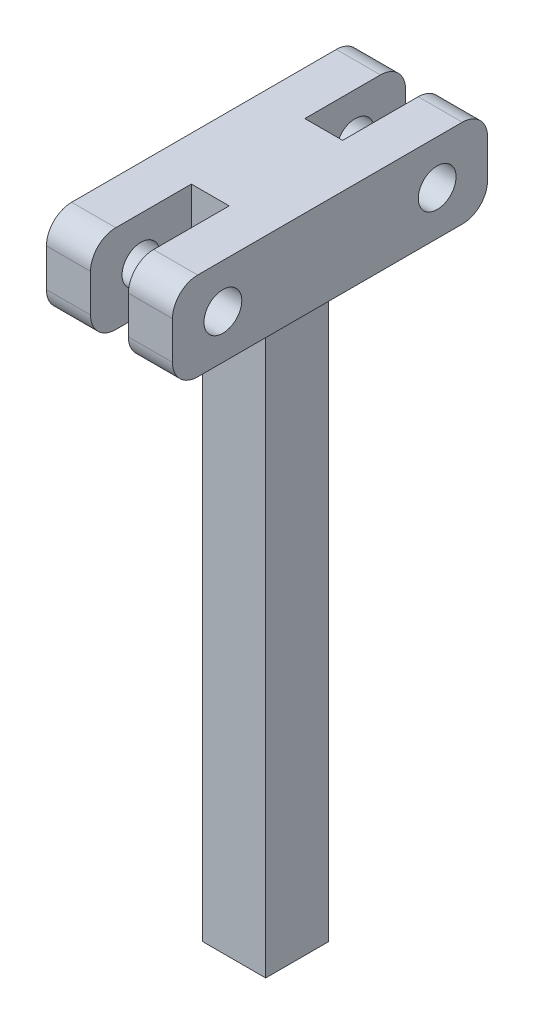
SolidWorks part; units mm, degrees
ref_plane "Alzado" through (0, 0, 0) normal (0, 0, 1) x (1, 0, 0)
ref_plane "Planta" through (0, 0, 0) normal (0, 1, 0) x (1, 0, 0)
ref_plane "Vista lateral" through (0, 0, 0) normal (1, 0, 0) x (0, 0, -1)
sketch "Croquis1" plane through (0, 0, 0) normal (0, 1, 0) x (1, 0, 0)
  line L1 (2.5, -2.6049) -> (-2.5, -2.6049)
  line L2 (2.5, -2.6049) -> (2.5, 2.3951)
  line L3 (2.5, 2.3951) -> (-2.5, 2.3951)
  line L4 (-2.5, -2.6049) -> (-2.5, 2.3951)
  line L5 (2.5, -2.6049) -> (-2.5, 2.3951) construction
  line L6 (2.5, 2.3951) -> (-2.5, -2.6049) construction
  dimension "D1" = 5
  dimension "D2" = 5
extrude "Saliente-Extruir1" add sketch "Croquis1" against normal blind 50
sketch "Croquis2" plane through (0, 0, 0) normal (1, 0, 0) x (0, 0, -1)
  line L1 (10.5, -3.5) -> (-10.5, -3.5)
  line L2 (12.5, -1.5) -> (12.5, 1.5)
  line L3 (10.5, 3.5) -> (-10.5, 3.5)
  line L4 (-12.5, -1.5) -> (-12.5, 1.5)
  line L5 (12.5, -3.5) -> (-12.5, 3.5) construction
  line L6 (12.5, 3.5) -> (-12.5, -3.5) construction
  arc A0 (-12.5, 1.5) -> (-10.5, 3.5) centre (-10.5, 1.5) cw
  arc A1 (-12.5, -1.5) -> (-10.5, -3.5) centre (-10.5, -1.5) ccw
  arc A2 (10.5, 3.5) -> (12.5, 1.5) centre (10.5, 1.5) cw
  arc A3 (12.5, -1.5) -> (10.5, -3.5) centre (10.5, -1.5) cw
  circle A4 centre (-8.5, 0) radius 1.5
  circle A5 centre (8.5, 0) radius 1.5
  point P0 (0, 0)
  dimension "D3" = 2
  dimension "D4" = 2
  dimension "D5" = 2
  dimension "D6" = 2
  dimension "D9" = 3
  dimension "D10" = 3
  dimension "D1" = 25
  dimension "D2" = 7
  dimension "D7" = 4
  dimension "D8" = 4
extrude "Saliente-Extruir2" add sketch "Croquis2" along normal mid plane 10
sketch "Croquis3" plane through (0, 3.5, 0) normal (0, 1, 0) x (1, 0, 0)
  line L0 (5, 12.5) -> (-5, 12.5) construction
  line L1 (-1.5, 4.5) -> (1.5, 4.5)
  line L2 (-1.5, 4.5) -> (-1.5, 12.5)
  line L3 (-1.5, 12.5) -> (1.5, 12.5)
  line L4 (1.5, 4.5) -> (1.5, 12.5)
  line L5 (-1.5, 4.5) -> (1.5, 12.5) construction
  line L6 (-1.5, 12.5) -> (1.5, 4.5) construction
  line L7 (5, -12.5) -> (-5, -12.5) construction
  line L8 (-1.5, -4.5) -> (1.5, -4.5)
  line L9 (-1.5, -4.5) -> (-1.5, -12.5)
  line L10 (-1.5, -12.5) -> (1.5, -12.5)
  line L11 (1.5, -4.5) -> (1.5, -12.5)
  line L12 (-1.5, -4.5) -> (1.5, -12.5) construction
  line L13 (-1.5, -12.5) -> (1.5, -4.5) construction
  point P0 (0, 8.5)
  point P7 (0, -8.5)
  dimension "D1" = 3
  dimension "D2" = 3
  dimension "D3" = 8
  dimension "D4" = 8
extrude "Cortar-Extruir1" cut sketch "Croquis3" against normal through all both and the other way through all
